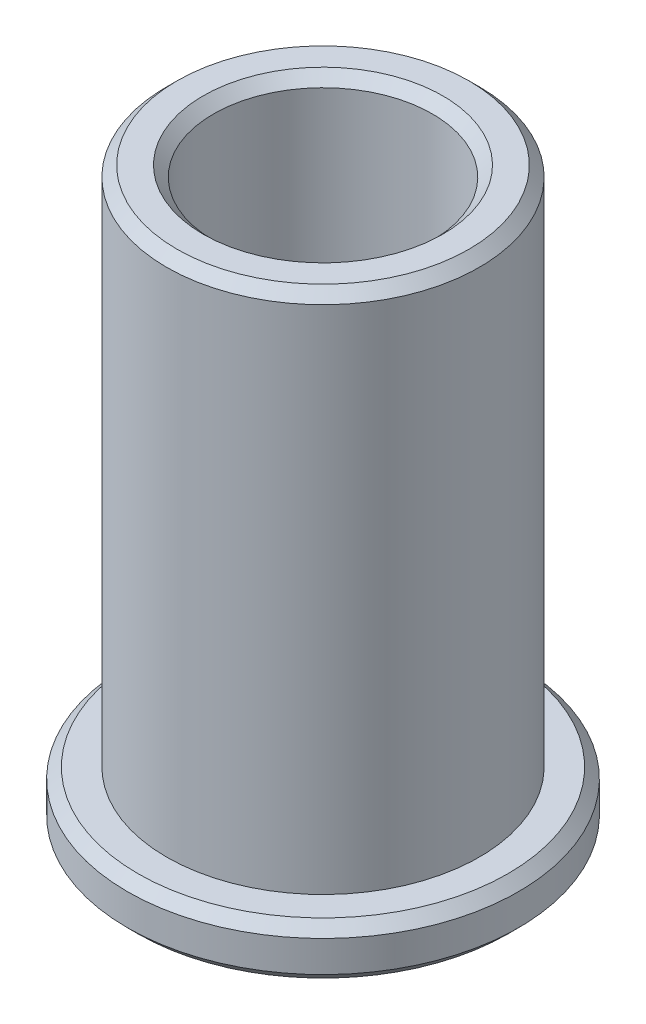
SolidWorks part; units mm, degrees
ref_plane "前视基准面" through (0, 0, 0) normal (0, 0, 1) x (1, 0, 0)
ref_plane "上视基准面" through (0, 0, 0) normal (0, 1, 0) x (1, 0, 0)
ref_plane "右视基准面" through (0, 0, 0) normal (1, 0, 0) x (0, 0, -1)
sketch "草图1" plane through (0, 0, 0) normal (0, 1, 0) x (1, 0, 0)
  circle A0 centre (0, 0) radius 3.75
  dimension "D1" = 7.5
extrude "凸台-拉伸1" add sketch "草图1" along normal blind 1
sketch "草图2" plane through (0, 1, 0) normal (0, 1, 0) x (1, 0, 0)
  circle A0 centre (0, 0) radius 3
  dimension "D1" = 6
extrude "凸台-拉伸2" add sketch "草图2" along normal blind 10
sketch "草图3" plane through (0, 11, 0) normal (0, 1, 0) x (1, 0, 0)
  circle A0 centre (0, 0) radius 2.1
  dimension "D1" = 4.2
extrude "切除-拉伸1" cut sketch "草图3" against normal through all
chamfer "倒角1" distance 0.2 angle 45 2 edges at (0, 1, 3.75) (0, 11, 3)
chamfer "倒角2" distance 0.2 angle 45 3 edges at (0, 11, 2.1) (0, 0, 2.1) (0, 0, 3.75)
equation "\"w10\"=1"
